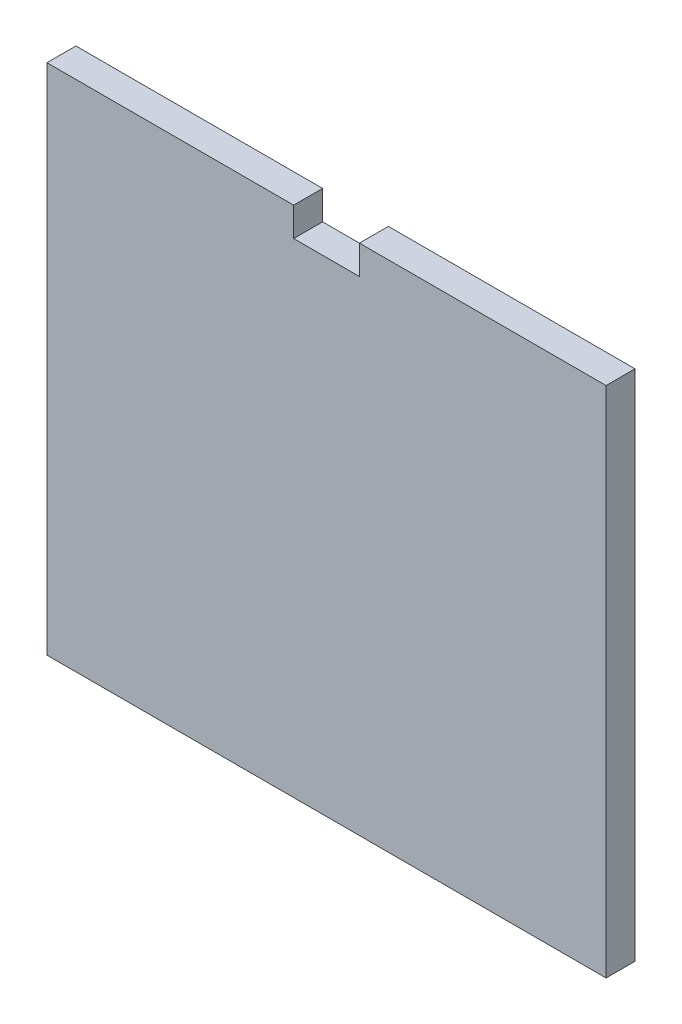
SolidWorks part; units mm, degrees
ref_plane "Front Plane" through (0, 0, 0) normal (0, 0, 1) x (1, 0, 0)
ref_plane "Top Plane" through (0, 0, 0) normal (0, 1, 0) x (1, 0, 0)
ref_plane "Right Plane" through (0, 0, 0) normal (1, 0, 0) x (0, 0, -1)
sketch "Sketch1" plane through (0, 0, 0) normal (0, 0, 1) x (1, 0, 0)
  line L0 (-6.35, 49.53) -> (-6.35, 43.942)
  line L1 (-53.975, -49.53) -> (53.975, -49.53)
  line L2 (-53.975, -49.53) -> (-53.975, 49.53)
  line L3 (-53.975, 49.53) -> (-6.35, 49.53)
  line L4 (53.975, -49.53) -> (53.975, 49.53)
  line L5 (-53.975, -49.53) -> (53.975, 49.53) construction
  line L6 (-53.975, 49.53) -> (53.975, -49.53) construction
  line L7 (-6.35, 43.942) -> (6.35, 43.942)
  line L8 (6.35, 43.942) -> (6.35, 49.53)
  line L9 (6.35, 49.53) -> (53.975, 49.53)
  point P0 (0, 0)
  dimension "D1" = 107.95
  dimension "D2" = 99.06
  dimension "D3" = 5.588
  dimension "D4" = 12.7
extrude "Boss-Extrude1" add sketch "Sketch1" along normal mid plane 5.588
